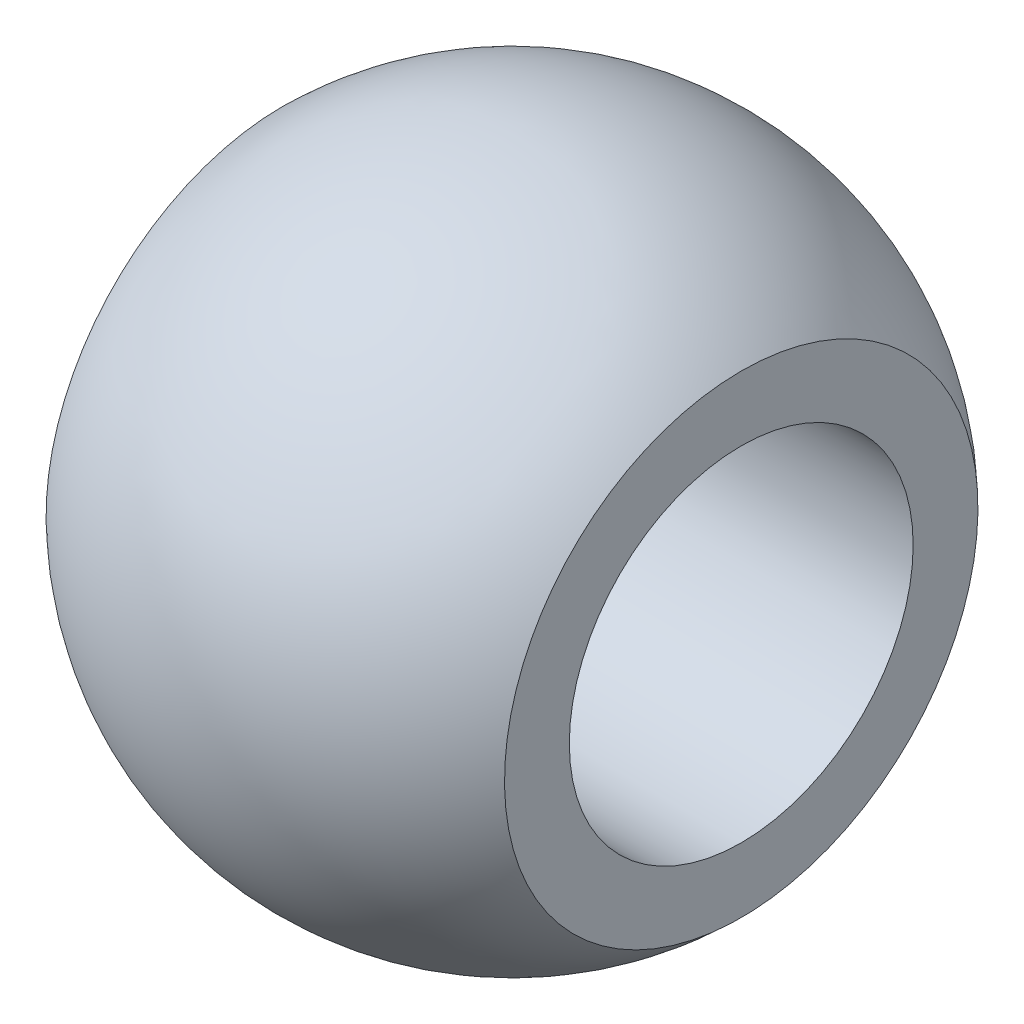
SolidWorks part; units mm, degrees
material "Cast Alloy Steel"
ref_plane "Front Plane" through (0, 0, 0) normal (0, 0, 1) x (1, 0, 0)
ref_plane "Top Plane" through (0, 0, 0) normal (0, 1, 0) x (1, 0, 0)
ref_plane "Right Plane" through (0, 0, 0) normal (1, 0, 0) x (0, 0, -1)
sketch "Sketch1" plane through (0, 0, 0) normal (0, 0, 1) x (1, 0, 0)
  line L0 (-9.1281, 0) -> (9.1281, 0) construction
  line L1 (-6.35, 4.7625) -> (6.35, 4.7625)
  line L2 (6.35, 0) -> (6.35, 6.5575)
  line L3 (-6.35, 0) -> (-6.35, 6.5575)
  arc A0 (6.35, 6.5575) -> (-6.35, 6.5575) centre (0, 0) ccw
  dimension "D1" = 18.2562
  dimension "D2" = 4.7625
  dimension "D3" = 6.35
  dimension "D4" = 6.35
revolve "Revolve1" add sketch "Sketch1" angle 360 about L0
sketch "Sketch2" plane through (0, 0, 0) normal (1, 0, 0) x (0, 0, -1)
  point P0 (0, 0)
